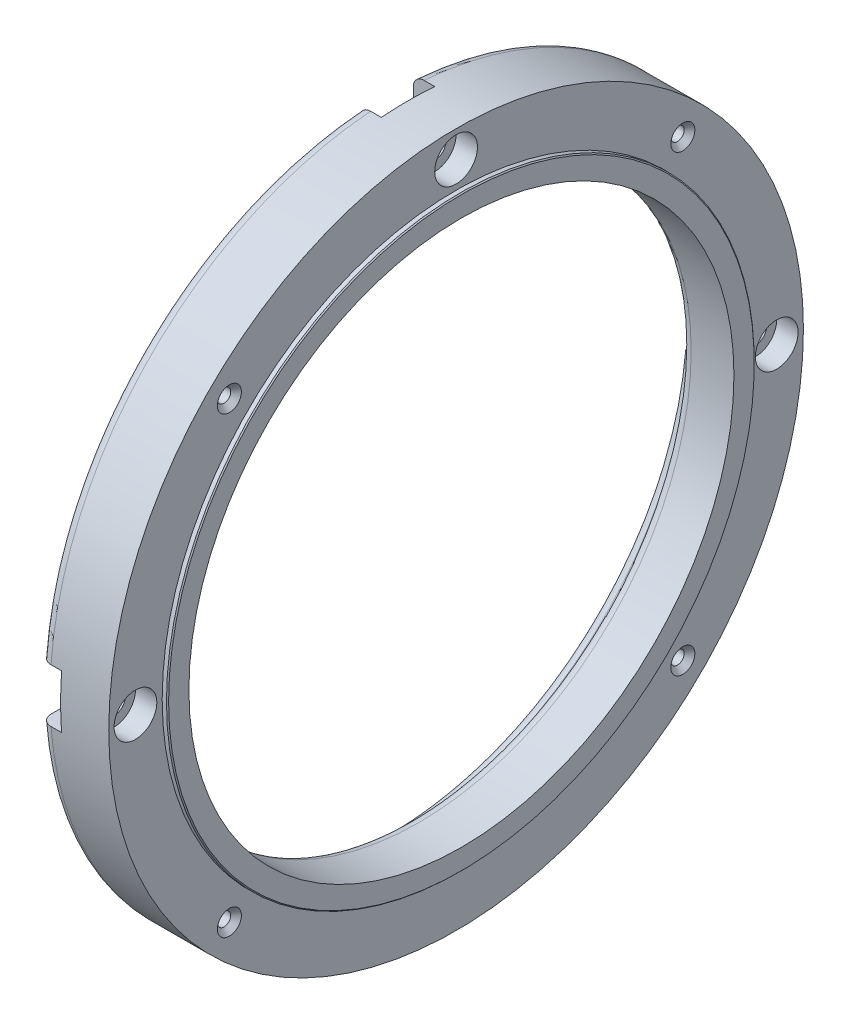
SolidWorks part; units mm, degrees
material "Alliage 6061"
ref_plane "Face" through (0, 0, 0) normal (0, 0, 1) x (1, 0, 0)
ref_plane "Dessus" through (0, 0, 0) normal (0, 1, 0) x (1, 0, 0)
ref_plane "Droite" through (0, 0, 0) normal (1, 0, 0) x (0, 0, -1)
sketch "Esquisse1" plane through (0, 0, 0) normal (0, 0, 1) x (1, 0, 0)
  line L0 (0, 0) -> (54.7909, 0) construction
  line L1 (0, 55) -> (0, 65)
  line L2 (0, 65) -> (13, 65)
  line L3 (13, 65) -> (13, 55)
  line L4 (13, 55) -> (14, 55)
  line L5 (4, 55) -> (4, 51)
  line L6 (4, 51) -> (14, 51)
  line L7 (0, 55) -> (4, 55)
  line L8 (14, 55) -> (14, 51)
  dimension "D1" = 110
  dimension "D2" = 10
  dimension "D3" = 102
  dimension "D4" = 130
  dimension "D5" = 13
  dimension "D6" = 110
  dimension "D7" = 1
revolve "Révolution1" add sketch "Esquisse1" angle 360 about L0
fillet "Congé1" radius 2 3 edges at (0, 0, 65) (0, 0, 55) (4, 0, 51)
sketch "Esquisse5" plane through (0, 0, 0) normal (-1, 0, 0) x (0, 0, 1)
  line L0 (-5, 80) -> (-5, 5)
  line L1 (-5, -5) -> (5, -5)
  line L2 (5, 80) -> (5, 5)
  line L4 (-5, 80) -> (5, 80)
  line L6 (-80, 5) -> (-5, 5)
  line L7 (-80, -5) -> (-5, -5)
  line L8 (80, 5) -> (80, -5)
  line L9 (-80, 5) -> (-80, -5)
  line L10 (5, 5) -> (80, 5)
  line L13 (5, -5) -> (80, -5)
  dimension "D1" = 5
  dimension "D2" = 5
  dimension "D3" = 5
  dimension "D4" = 5
extrude "Enlèv. mat.-Extru.1" cut sketch "Esquisse5" against normal blind 4
sketch "Esquisse6" plane through (14, 0, 0) normal (1, 0, 0) x (0, 0, -1)
  line L0 (0, 60) -> (0, -60) construction
  line L1 (-60, 0) -> (60, 0) construction
  line L2 (42.4264, 42.4264) -> (-42.4264, -42.4264) construction
  line L3 (-42.4264, 42.4264) -> (42.4264, -42.4264) construction
  circle A0 centre (0, 0) radius 60 construction
  dimension "D1" = 120
  dimension "D2" = 45
  dimension "D3" = 45
hole_wizard "Chambrage pour vis à tête hexagonale M41" positions "Esquisse10" profile "Esquisse9" counterbore size "M4" standard "Iso" end condition through all
sketch "Esquisse10" plane through (14, 0, 0) normal (1, 0, 0) x (0, 0, -1)
  point P3 (60, 0)
  point P14 (-60, 0)
  point P19 (0, 60)
sketch "Esquisse9" plane through (14, 0, -60) normal (0, 1, 0) x (0, 0, -1)
  line L0 (0, 0) -> (0, 14)
  line L1 (0, 14) -> (2.15, 14)
  line L3 (2.15, 14) -> (2.15, 5)
  line L4 (2.15, 5) -> (4, 5)
  line L5 (4, 5) -> (4, 0)
  line L7 (4, 0) -> (0, 0)
  line L11 (0, -6.35) -> (0, 107.95) construction
  dimension "Diamètre du perçage jusqu'au prochain" = 4.3
  dimension "Profondeur du perçage jusqu'au prochain" = 14
  dimension "Diamètre du chambrage" = 8
  dimension "Profondeur du chambrage" = 5
chamfer "Chanfrein1" distance 0.2 angle 45 1 edges at (14, 0, 55)
hole_wizard "Trou taraudé M31" positions "Esquisse12" profile "Esquisse11" tap size "M3" standard "Iso" end condition up to next
sketch "Esquisse12" plane through (13, 0, 0) normal (1, 0, 0) x (0, 0, -1)
  point P0 (-42.4264, 42.4264)
  point P3 (42.4264, 42.4264)
  point P6 (42.4264, -42.4264)
  point P9 (-42.4264, -42.4264)
cosmetic thread "Filetage de perçage1" parameters "D2"=3
cosmetic thread "Filetage de perçage2" parameters "D2"=3
cosmetic thread "Filetage de perçage3" parameters "D2"=3
cosmetic thread "Filetage de perçage4" parameters "D2"=3
sketch "Esquisse11" plane through (13, 42.4264, 42.4264) normal (0, 1, 0) x (0, 0, -1)
  line L0 (0, 0) -> (0, 13)
  line L1 (0, 13) -> (1.25, 13)
  line L2 (1.25, 13) -> (1.25, 1)
  line L3 (1.25, 1) -> (2.25, 0)
  line L5 (2.25, 0) -> (0, 0)
  line L6 (-1.25, 1) -> (-2.25, 0) construction
  line L11 (0, -6.35) -> (0, 107.95) construction
  dimension "Diamètre du trou pour taraudage jusqu'au prochain" = 2.5
  dimension "Profondeur du trou pour taraudage jusqu'au prochain" = 13
  dimension "Diamètre du fraisage entrant" = 4.5
  dimension "Angle du fraisage entrant" = 90
